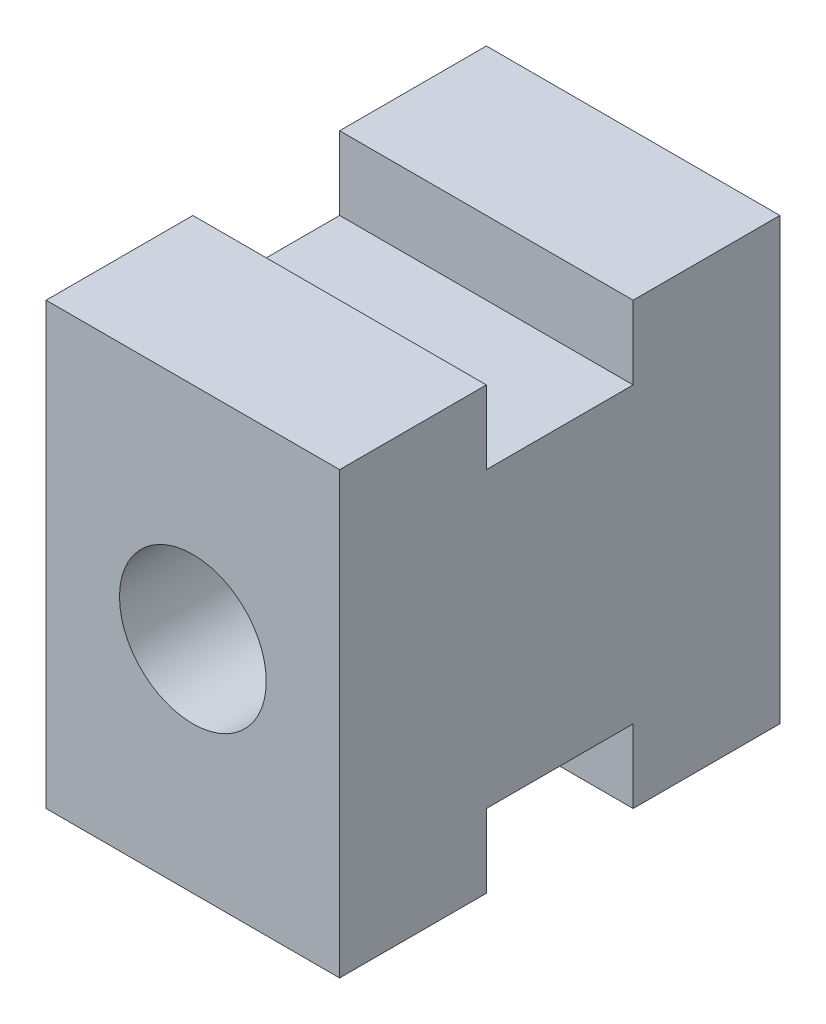
SolidWorks part; units mm, degrees
ref_plane "前视基准面" through (0, 0, 0) normal (0, 0, 1) x (1, 0, 0)
ref_plane "上视基准面" through (0, 0, 0) normal (0, 1, 0) x (1, 0, 0)
ref_plane "右视基准面" through (0, 0, 0) normal (1, 0, 0) x (0, 0, -1)
sketch "草图1" plane through (0, 0, 0) normal (0, 0, 1) x (1, 0, 0)
  line L1 (2, 3) -> (-2, 3)
  line L2 (2, 3) -> (2, -3)
  line L3 (2, -3) -> (-2, -3)
  line L4 (-2, 3) -> (-2, -3)
  line L5 (2, 3) -> (-2, -3) construction
  line L6 (2, -3) -> (-2, 3) construction
  circle A0 centre (0, 0) radius 1
  point P0 (0, 0)
  dimension "D3" = 2
  dimension "D1" = 4
  dimension "D2" = 6
extrude "凸台-拉伸1" add sketch "草图1" along normal blind 6
sketch "草图2" plane through (2, 0, 0) normal (1, 0, 0) x (0, 0, -1)
  line L0 (-4, 3) -> (-4, -3)
  line L1 (-6, 3) -> (0, 3) construction
  line L2 (-6, -3) -> (0, -3) construction
  line L3 (-2, 3) -> (-2, -3)
  line L4 (-6, -3) -> (-6, 3) construction
  line L5 (0, -3) -> (0, 3) construction
  line L6 (-4, 2) -> (-2, 2)
  line L7 (-4, -2) -> (-2, -2)
  line L8 (-4, 3) -> (-2, 3)
  line L9 (-4, -3) -> (-2, -3)
  line M6 (0, 3) -> (-6, 3)
  line M8 (-6, -3) -> (0, -3)
  dimension "D1" = 2
  dimension "D2" = 2
  dimension "D3" = 1
  dimension "D4" = 1
extrude "切除-拉伸1" cut sketch "草图2" against normal through all contours L0 L6 L3 M6 | L7 L0 L3 M8
